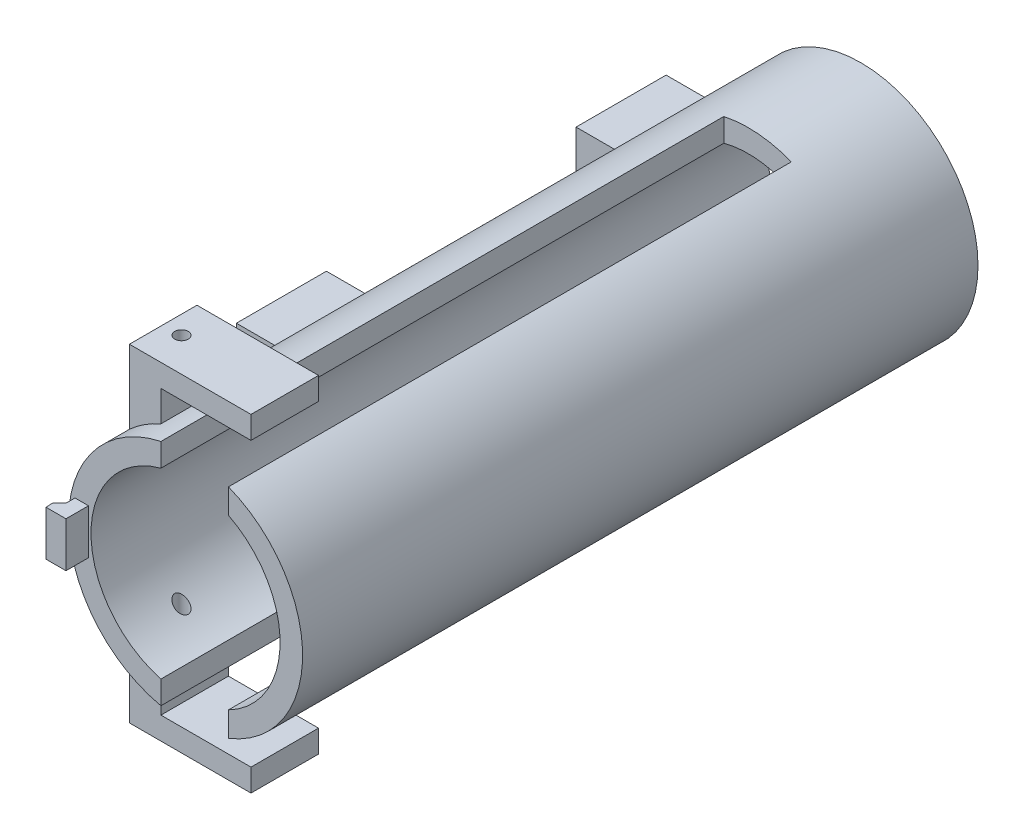
SolidWorks part; units mm, degrees
ref_plane "Plano frontal" through (0, 0, 0) normal (0, 0, 1) x (1, 0, 0)
ref_plane "Plano superior" through (0, 0, 0) normal (0, 1, 0) x (1, 0, 0)
ref_plane "Plano direito" through (0, 0, 0) normal (1, 0, 0) x (0, 0, -1)
sketch "Esboço1" plane through (0, 0, 0) normal (0, 0, 1) x (1, 0, 0)
  circle A0 centre (0, 0) radius 21
  circle A1 centre (0, 0) radius 26
  dimension "D1" = 5
  dimension "D2" = 42
extrude "Ressalto-extrusão1" add sketch "Esboço1" along normal blind 150
sketch3d "3DSketch1"
  point P0 (3.6336, -25.7448, 55.7114)
ref_plane "Plano1" through (0, -27.2211, 0) normal (0, -1, 0) x (0, 0, -1)
sketch "Esboço3" plane through (0, -27.2211, 0) normal (0, -1, 0) x (0, 0, -1)
  line L0 (-150, -5.4656) -> (-150, 9.5344)
  line L1 (-150, 26) -> (-150, -26) construction
  line L2 (-150, 9.5344) -> (-25, 9.5344)
  line L3 (-25, 9.5344) -> (-25, -5.4656)
  line L4 (-25, -5.4656) -> (-150, -5.4656)
  line L5 (0, -26) -> (0, 26) construction
  point P5 (-150, 2.0344)
  dimension "D1" = 15
  dimension "D2" = 25
extrude "Corte-extrusão1" cut sketch "Esboço3" against normal through all both and the other way through all
sketch "Esboço4" plane through (0, -27.2211, 0) normal (0, -1, 0) x (0, 0, -1)
  line L0 (-25, -5.4656) -> (-150, -5.4656) construction
  line L1 (-145, -10.4656) -> (-130, -10.4656)
  line L2 (-145, -10.4656) -> (-145, -17.4656)
  line L3 (-145, -17.4656) -> (-130, -17.4656)
  line L4 (-130, -10.4656) -> (-130, -17.4656)
  line L5 (-150, -5.4656) -> (-150, -26) construction
  dimension "D1" = 5
  dimension "D2" = 5
  dimension "D3" = 15
  dimension "D4" = 7
extrude "Ressalto-extrusão2" add sketch "Esboço4" against normal up to next
sketch "Esboço5" plane through (0, -27.2211, 0) normal (0, -1, 0) x (1, 0, 0)
  line L1 (-10.4656, 145) -> (-17.4656, 145)
  line L2 (-10.4656, 145) -> (-10.4656, 130)
  line L3 (-10.4656, 130) -> (-17.4656, 130)
  line L4 (-17.4656, 145) -> (-17.4656, 130)
extrude "Ressalto-extrusão3" add sketch "Esboço5" along normal blind 10
sketch "Esboço6" plane through (-10.4656, 0, 0) normal (1, 0, 0) x (0, 0, -1)
  line L0 (-130, -23.8007) -> (-130, -37.2211) construction
  line L1 (-145, -37.2211) -> (-130, -37.2211)
  line L2 (-145, -37.2211) -> (-145, -32.2211)
  line L3 (-145, -32.2211) -> (-130, -32.2211)
  line L4 (-130, -37.2211) -> (-130, -32.2211)
  dimension "D1" = 5
extrude "Ressalto-extrusão4" add sketch "Esboço6" along normal blind 20
sketch3d "3DSketch2"
  point P0 (4.427, 25.6203, 12.7577)
ref_plane "Plano3" through (0, 25.6203, 0) normal (0, 1, 0) x (0, 0, 1)
sketch "Esboço7" plane through (0, 25.6203, 0) normal (0, 1, 0) x (0, 0, 1)
  line L0 (150, -26) -> (150, -5.4656) construction
  line L1 (130, -10.4656) -> (145, -10.4656)
  line L2 (130, -10.4656) -> (130, -17.4656)
  line L3 (130, -17.4656) -> (145, -17.4656)
  line L4 (145, -10.4656) -> (145, -17.4656)
  line L5 (150, -5.4656) -> (25, -5.4656) construction
  dimension "D1" = 15
  dimension "D2" = 5
  dimension "D3" = 5
  dimension "D4" = 7
extrude "Ressalto-extrusão5" add sketch "Esboço7" against normal up to next
sketch "Esboço8" plane through (0, 25.6203, 0) normal (0, 1, 0) x (1, 0, 0)
  line L1 (-17.4656, -130) -> (-10.4656, -130)
  line L2 (-17.4656, -130) -> (-17.4656, -145)
  line L3 (-17.4656, -145) -> (-10.4656, -145)
  line L4 (-10.4656, -130) -> (-10.4656, -145)
extrude "Ressalto-extrusão6" add sketch "Esboço8" along normal blind 10
sketch "Esboço9" plane through (-10.4656, 0, 0) normal (1, 0, 0) x (0, 0, -1)
  line L5 (-130, 23.8007) -> (-130, 35.6203) construction
  line L6 (-145, 35.6203) -> (-130, 35.6203)
  line L7 (-145, 35.6203) -> (-145, 30.6203)
  line L8 (-145, 30.6203) -> (-130, 30.6203)
  line L9 (-130, 35.6203) -> (-130, 30.6203)
  dimension "D1" = 5
extrude "Ressalto-extrusão7" add sketch "Esboço9" along normal blind 20
sketch "Esboço10" plane through (0, -37.2211, 0) normal (0, -1, 0) x (1, 0, 0)
  line L0 (-17.4656, 137.5) -> (9.5344, 137.5) construction
  line L1 (-17.4656, 145) -> (-17.4656, 130) construction
  line L2 (9.5344, 145) -> (9.5344, 130) construction
  circle A0 centre (-13.4052, 137.5) radius 1.5
extrude "Corte-extrusão2" cut sketch "Esboço10" against normal through all both and the other way through all
sketch3d "3DSketch3"
  point P0 (-25.9916, -0.662, 86.0184)
ref_plane "Plano4" through (-25.9916, 0, 0) normal (-1, 0, 0) x (0, -1, 0)
sketch "Esboço14" plane through (-25.9916, 0, 0) normal (-1, 0, 0) x (0, -1, 0)
  line L0 (-19.2601, 130) -> (-19.2601, 0) construction
  line L1 (-26, 0) -> (26, 0) construction
  line L2 (-19.2601, 130) -> (19.2601, 130) construction
  line L3 (19.2601, 130) -> (19.2601, 0) construction
  line L4 (19.2601, 0) -> (-19.2601, 0) construction
  line L5 (0, 130) -> (0, 0) construction
  line L6 (-19.2601, 112.7211) -> (-4.2601, 112.7211)
  line L7 (-19.2601, 112.7211) -> (-19.2601, 92.7211)
  line L8 (-19.2601, 92.7211) -> (-4.2601, 92.7211)
  line L9 (-4.2601, 112.7211) -> (-4.2601, 92.7211)
  line L10 (-19.2601, 65) -> (19.2601, 65) construction
  line L11 (19.2601, 92.7211) -> (4.2601, 92.7211)
  line L12 (4.2601, 112.7211) -> (4.2601, 92.7211)
  line L13 (19.2601, 112.7211) -> (4.2601, 112.7211)
  line L14 (19.2601, 112.7211) -> (19.2601, 92.7211)
  line L15 (19.2601, 17.2789) -> (19.2601, 37.2789)
  line L16 (19.2601, 17.2789) -> (4.2601, 17.2789)
  line L17 (4.2601, 17.2789) -> (4.2601, 37.2789)
  line L18 (19.2601, 37.2789) -> (4.2601, 37.2789)
  line L19 (-19.2601, 37.2789) -> (-4.2601, 37.2789)
  line L20 (-4.2601, 17.2789) -> (-4.2601, 37.2789)
  line L21 (-19.2601, 17.2789) -> (-4.2601, 17.2789)
  line L22 (-19.2601, 17.2789) -> (-19.2601, 37.2789)
  dimension "D1" = 15
  dimension "D2" = 20
extrude "Ressalto-extrusão8" add sketch "Esboço14" against normal up to next
sketch "Esboço15" plane through (-25.9916, 0, 0) normal (-1, 0, 0) x (0, 0, 1)
  line L0 (17.2789, 11.7601) -> (112.7211, 11.7601) construction
  line L1 (17.2789, 19.2601) -> (17.2789, 4.2601) construction
  line L2 (112.7211, 4.2601) -> (112.7211, 19.2601) construction
  line L3 (102.7211, 19.2601) -> (102.7211, -19.2601) construction
  line L4 (112.7211, 19.2601) -> (92.7211, 19.2601) construction
  line L5 (92.7211, -19.2601) -> (112.7211, -19.2601) construction
  line L6 (112.7211, -11.7601) -> (17.2789, -11.7601) construction
  line L7 (112.7211, -19.2601) -> (112.7211, -4.2601) construction
  line L8 (17.2789, -4.2601) -> (17.2789, -19.2601) construction
  line L9 (27.2789, 19.2601) -> (27.2789, -19.2601) construction
  line L10 (37.2789, 19.2601) -> (17.2789, 19.2601) construction
  line L11 (17.2789, -19.2601) -> (37.2789, -19.2601) construction
  line L12 (65, 41.4744) -> (65, -47.7689) construction
  line L13 (-11.4678, 0) -> (157.6888, 0) construction
  line L14 (150, -25.419) -> (150, 25.419) construction
  line L15 (0, 26) -> (0, -26) construction
  circle A0 centre (27.2789, 11.7601) radius 1.75
  circle A1 centre (102.7211, 11.7601) radius 1.75
  circle A2 centre (102.7211, -11.7601) radius 1.75
  circle A3 centre (27.2789, -11.7601) radius 1.75
  dimension "D1" = 47.2789
  dimension "D2" = 23.5203
  dimension "D3" = 75.4423
  dimension "D4" = 27.2789
  dimension "D5" = 38.5203
extrude "Corte-extrusão3" cut sketch "Esboço15" against normal blind 15
sketch "Esboço17" plane through (0, -27.2211, 0) normal (0, -1, 0) x (0, 0, -1)
  line L0 (-25, 2.0344) -> (0, 2.0344) construction
  line L1 (-25, 9.5344) -> (-25, -5.4656) construction
  line L2 (0, -26) -> (0, 26) construction
  circle A0 centre (-19, 2.0344) radius 1.75
  circle A1 centre (-6, 2.0344) radius 1.75
  dimension "D1" = 6
  dimension "D2" = 13
extrude "Corte-extrusão4" cut sketch "Esboço17" along normal blind 3 and the other way blind 18
sketch3d "3DSketch4"
  point P0 (2.6209, 20.8358, 10.7292)
ref_plane "Plano5" through (0, 20.8358, 0) normal (0, 1, 0) x (0, 0, 1)
sketch "Esboço18" plane through (0, 20.8358, 0) normal (0, 1, 0) x (0, 0, 1)
  line L1 (9, 0.3024) -> (9, 3.7665)
  line L2 (9, 3.7665) -> (6, 5.4985)
  line L3 (6, 5.4985) -> (3, 3.7665)
  line L4 (3, 3.7665) -> (3, 0.3024)
  line L5 (3, 0.3024) -> (6, -1.4297)
  line L6 (6, -1.4297) -> (9, 0.3024)
  line L7 (21.989, 3.7853) -> (18.9782, 5.4984)
  line L8 (18.9782, 5.4984) -> (15.9891, 3.7475)
  line L9 (15.9891, 3.7475) -> (16.011, 0.2835)
  line L10 (16.011, 0.2835) -> (19.0218, -1.4296)
  line L11 (19.0218, -1.4296) -> (22.0109, 0.3213)
  line L12 (22.0109, 0.3213) -> (21.989, 3.7853)
  circle A0 centre (6, 2.0344) radius 3 construction
  circle A1 centre (19, 2.0344) radius 3 construction
  dimension "D1" = 6
  dimension "D2" = 6
extrude "Corte-extrusão5" cut sketch "Esboço18" against normal blind 3.5 from offset 41.1 offset against normal yes
sketch "Esboço19" plane through (0, 0, 150) normal (0, 0, 1) x (1, 0, 0)
  line L0 (-25.9916, 0) -> (26, 0) construction
  line L1 (-25.9916, 53.8209) -> (-25.9916, -53.8209) construction
  line L2 (-24.5572, 5) -> (-21.5572, 5)
  line L3 (-25.5572, 5) -> (-21.5572, 5)
  line L4 (-25.5572, 5) -> (-25.5572, -5)
  line L5 (-25.5572, -5) -> (-21.5572, -5)
  line L6 (-21.5572, 5) -> (-21.5572, -5)
  line L7 (-21.5572, 5) -> (-24.5572, 5)
  line L8 (-21.5572, 5) -> (-21.5572, -5)
  line L9 (-21.5572, -5) -> (-24.5572, -5)
  line L10 (-24.5572, 5) -> (-24.5572, -5)
  arc A0 (9.5344, -24.1887) -> (9.5344, 24.1887) centre (0, 0) ccw construction
  dimension "D1" = 10
  dimension "D2" = 5
  dimension "D3" = 4
  dimension "D4" = 3
extrude "Ressalto-extrusão9" add sketch "Esboço19" along normal blind 5 contours L10 L0 L6 L2 | L0 L10 L5 L8
sketch "Esboço20" plane through (0, 5, 0) normal (0, 1, 0) x (1, 0, 0)
  line L0 (-24.5572, -155) -> (-24.5572, -152)
  line L1 (-24.5572, -155) -> (-24.5572, -150) construction
  line L2 (-24.5572, -152) -> (-27.5572, -155)
  line L3 (-27.5572, -155) -> (-24.5572, -155)
  dimension "D1" = 3
  dimension "D2" = 3
extrude "Ressalto-extrusão10" add sketch "Esboço20" against normal blind 10 contours L3 L0 L2
sketch "Esboço23" plane through (0, -5, 0) normal (0, -1, 0) x (1, 0, 0)
  line L0 (-27.5572, 155) -> (-25.9916, 155)
  line L1 (-25.9916, 53.8209) -> (-25.9916, -53.8209) construction
  line L2 (-27.5572, 155) -> (-21.5572, 155) construction
  line L3 (-25.9916, 155) -> (-26.0572, 153.5)
  line L4 (-24.5572, 152) -> (-27.5572, 155) construction
  line L5 (-26.0572, 153.5) -> (-27.5572, 155)
extrude "Corte-extrusão6" cut sketch "Esboço23" against normal through all contours L5 L0 L3
